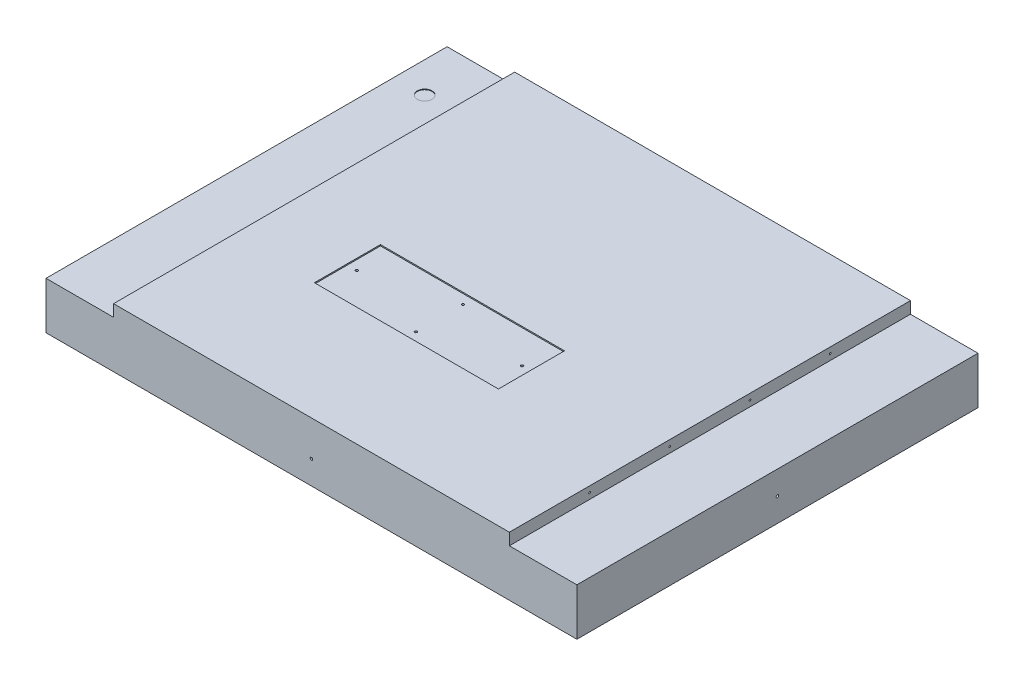
SolidWorks part; units mm, degrees
material "1.4511 (X3CrNb17)"
ref_plane "前视基准面" through (0, 0, 0) normal (0, 0, 1) x (1, 0, 0)
ref_plane "上视基准面" through (0, 0, 0) normal (0, 1, 0) x (1, 0, 0)
ref_plane "右视基准面" through (0, 0, 0) normal (1, 0, 0) x (0, 0, -1)
sketch "草图1" plane through (0, 0, 0) normal (0, 1, 0) x (1, 0, 0)
  line L1 (-450, 340) -> (450, 340)
  line L2 (-450, 340) -> (-450, -340)
  line L3 (-450, -340) -> (450, -340)
  line L4 (450, 340) -> (450, -340)
  line L5 (-450, 340) -> (450, -340) construction
  line L6 (-450, -340) -> (450, 340) construction
  point P0 (0, 0)
  dimension "D1" = 900
  dimension "D2" = 680
extrude "凸台-拉伸1" add sketch "草图1" along normal blind 80
sketch "草图2" plane through (0, 80, 0) normal (0, 1, 0) x (1, 0, 0)
  line L1 (-335.5, 340) -> (335.5, 340)
  line L2 (-335.5, 340) -> (-335.5, -340)
  line L3 (-335.5, -340) -> (335.5, -340)
  line L4 (335.5, 340) -> (335.5, -340)
  line L5 (-335.5, 340) -> (335.5, -340) construction
  line L6 (-335.5, -340) -> (335.5, 340) construction
  point P0 (0, 0)
  dimension "D1" = 671
  dimension "D2" = 680
extrude "凸台-拉伸2" add sketch "草图2" along normal blind 20
sketch "草图3" plane through (0, 0, 340) normal (0, 0, 1) x (1, 0, 0)
  line L0 (-335.5, 100) -> (-335.5, 80) construction
  point P0 (-327.5, 50)
  point P3 (-196.5, 50)
  point P5 (-65.5, 50)
  point P6 (65.5, 50)
  point P7 (196.5, 50)
  point P8 (327.5, 50)
  dimension "D1" = 8
  dimension "D2" = 6
sketch "草图4" plane through (0, 100, 0) normal (0, 1, 0) x (1, 0, 0)
  line L1 (-196, -27) -> (116, -27)
  line L2 (-196, -27) -> (-196, -139)
  line L3 (-196, -139) -> (116, -139)
  line L4 (116, -27) -> (116, -139)
  point P0 (0, 0)
  dimension "D1" = 312
  dimension "D2" = 112
extrude "切除-拉伸1" cut sketch "草图4" against normal blind 2
sketch "草图5" plane through (-335.5, 0, 0) normal (-1, 0, 0) x (0, 0, 1)
  line L0 (340, 100) -> (340, 80) construction
  point P0 (247.4, 50)
  point P4 (114.6, 50)
  point P5 (-18.2, 50)
  point P6 (-151, 50)
  point P7 (-283.8, 50)
  dimension "D1" = 92.6
  dimension "D2" = 5
sketch "草图6" plane through (0, 100, 0) normal (0, 1, 0) x (1, 0, 0)
  line L1 (-180, -43) -> (100, -43) construction
  line L2 (-180, -43) -> (-180, -123) construction
  line L3 (-180, -123) -> (100, -123) construction
  line L4 (100, -43) -> (100, -123) construction
  point P0 (0, 0)
  point P6 (100, -83)
  point P7 (-180, -83)
  point P8 (-40, -123)
  point P9 (-40, -43)
  dimension "D1" = 280
  dimension "D2" = 80
hole_wizard "M5 螺纹孔1" positions "草图7" profile "草图8" tap size "M5" standard "GB"
sketch "草图7" plane through (0, 100, 0) normal (0, 1, 0) x (1, 0, 0)
  point P0 (-180, -83)
  point P3 (-40, -43)
  point P6 (-40, -123)
  point P9 (100, -83)
cosmetic thread "孔螺蚊线1" parameters "D1"=60, "D2"=5
cosmetic thread "孔螺蚊线2" parameters "D1"=60, "D2"=5
cosmetic thread "孔螺蚊线3" parameters "D1"=60, "D2"=5
cosmetic thread "孔螺蚊线4" parameters "D1"=60, "D2"=5
sketch "草图8" plane through (-180, 100, 83) normal (1, 0, 0) x (0, 0, 1)
  line L0 (0, 0) -> (0, 10.2618)
  line L1 (0, 10.2618) -> (2.1, 9)
  line L2 (2.1, 9) -> (2.1, 0)
  line L5 (2.1, 0) -> (0, 0)
  line L10 (0, 10.2618) -> (-2.1, 9) construction
  line L11 (0, -6.35) -> (0, 107.95) construction
  dimension "螺纹孔钻头直径" = 4.2
  dimension "螺纹孔钻头深度" = 9
  dimension "导头角度" = 118
ref_plane "基准面1" through (0, 40, 0) normal (0, 1, 0) x (1, 0, 0)
ref_plane "基准面2" through (450, 0, 0) normal (1, 0, 0) x (0, 0, -1)
ref_plane "基准面3" through (-450, 0, 0) normal (1, 0, 0) x (0, 0, -1)
ref_plane "基准面4" through (0, 0, -340) normal (0, 0, 1) x (1, 0, 0)
ref_plane "基准面5" through (0, 0, 340) normal (0, 0, 1) x (1, 0, 0)
sketch "草图9" plane through (0, 0, 340) normal (0, 0, 1) x (1, 0, 0)
  line L0 (-450, 80) -> (-450, 0) construction
  point P0 (0, 40)
  dimension "D1" = 450
hole_wizard "M5 螺纹孔2" positions "草图10" profile "草图11" tap size "M5" standard "GB" end condition through all
sketch "草图10" plane through (0, 0, 340) normal (0, 0, 1) x (1, 0, 0)
  point P0 (0, 40)
sketch "草图11" plane through (0, 40, 340) normal (1, 0, 0) x (0, -1, 0)
  line L0 (0, 0) -> (0, 680)
  line L1 (0, 680) -> (2.1, 680)
  line L2 (2.1, 680) -> (2.1, 0)
  line L5 (2.1, 0) -> (0, 0)
  line L11 (0, -6.35) -> (0, 107.95) construction
  dimension "通孔螺纹孔钻头直径" = 4.2
  dimension "通孔螺纹孔钻头深度" = 680
cosmetic thread "孔螺蚊线5" parameters "D2"=5
sketch "草图12" plane through (-450, 0, 0) normal (-1, 0, 0) x (0, 0, 1)
  line L0 (340, 80) -> (340, 0) construction
  point P0 (0, 40)
  dimension "D1" = 340
hole_wizard "M5 螺纹孔3" positions "草图13" profile "草图14" tap size "M5" standard "GB" end condition through all
sketch "草图13" plane through (-450, 0, 0) normal (-1, 0, 0) x (0, 0, 1)
  point P0 (0, 40)
sketch "草图14" plane through (-450, 40, 0) normal (0, 1, 0) x (0, 0, 1)
  line L0 (0, 0) -> (0, 900)
  line L1 (0, 900) -> (2.1, 900)
  line L2 (2.1, 900) -> (2.1, 0)
  line L5 (2.1, 0) -> (0, 0)
  line L11 (0, -6.35) -> (0, 107.95) construction
  dimension "通孔螺纹孔钻头直径" = 4.2
  dimension "通孔螺纹孔钻头深度" = 900
cosmetic thread "孔螺蚊线6" parameters "D2"=5
sketch "草图15" plane through (0, 80, 0) normal (0, 1, 0) x (1, 0, 0)
  line L0 (-335.5, 340) -> (-450, 340) construction
  line L1 (-450, 340) -> (-450, -340) construction
  circle A0 centre (-398, 250) radius 12.5
  point P9 (-398, 250)
  dimension "D1" = 25
  dimension "D2" = 90
  dimension "D3" = 52
extrude "切除-拉伸2" cut sketch "草图15" against normal blind 1
sketch "草图16" plane through (-335.5, 0, 0) normal (-1, 0, 0) x (0, 0, 1)
  line L0 (-340, 100) -> (340, 100) construction
  line L1 (-340, 100) -> (-340, 80) construction
  point P0 (-204, 90)
  point P7 (-68, 90)
  point P8 (68, 90)
  point P9 (204, 90)
  dimension "D1" = 10
  dimension "D2" = 136
  dimension "D3" = 4
hole_wizard "M3.5 螺纹孔1" positions "草图17" profile "草图19" tap size "M3.5" standard "GB"
sketch "草图17" plane through (-335.5, 0, 0) normal (-1, 0, 0) x (0, 0, 1)
  point P0 (-204, 90)
  point P3 (-68, 90)
  point P6 (68, 90)
  point P9 (204, 90)
sketch "草图19" plane through (-335.5, 90, -204) normal (0, 1, 0) x (0, 0, 1)
  line L0 (0, 0) -> (0, 8.2712)
  line L1 (0, 8.2712) -> (1.45, 7.4)
  line L2 (1.45, 7.4) -> (1.45, 0)
  line L5 (1.45, 0) -> (0, 0)
  line L10 (0, 8.2712) -> (-1.45, 7.4) construction
  line L11 (0, -6.35) -> (0, 107.95) construction
  dimension "螺纹孔钻头直径" = 2.9
  dimension "螺纹孔钻头深度" = 7.4
  dimension "导头角度" = 118
cosmetic thread "孔螺蚊线7" parameters "D1"=4.4, "D2"=3.5
cosmetic thread "孔螺蚊线8" parameters "D1"=4.4, "D2"=3.5
cosmetic thread "孔螺蚊线9" parameters "D1"=4.4, "D2"=3.5
cosmetic thread "孔螺蚊线10" parameters "D1"=4.4, "D2"=3.5
mirror "镜向1" about plane through (0, 0, 0) normal (1, 0, 0) of "M3.5 螺纹孔1"
cosmetic thread "孔螺蚊线11" parameters "D1"=4.4, "D2"=3.5
cosmetic thread "孔螺蚊线12" parameters "D1"=4.4, "D2"=3.5
cosmetic thread "孔螺蚊线13" parameters "D1"=4.4, "D2"=3.5
cosmetic thread "孔螺蚊线14" parameters "D1"=4.4, "D2"=3.5
